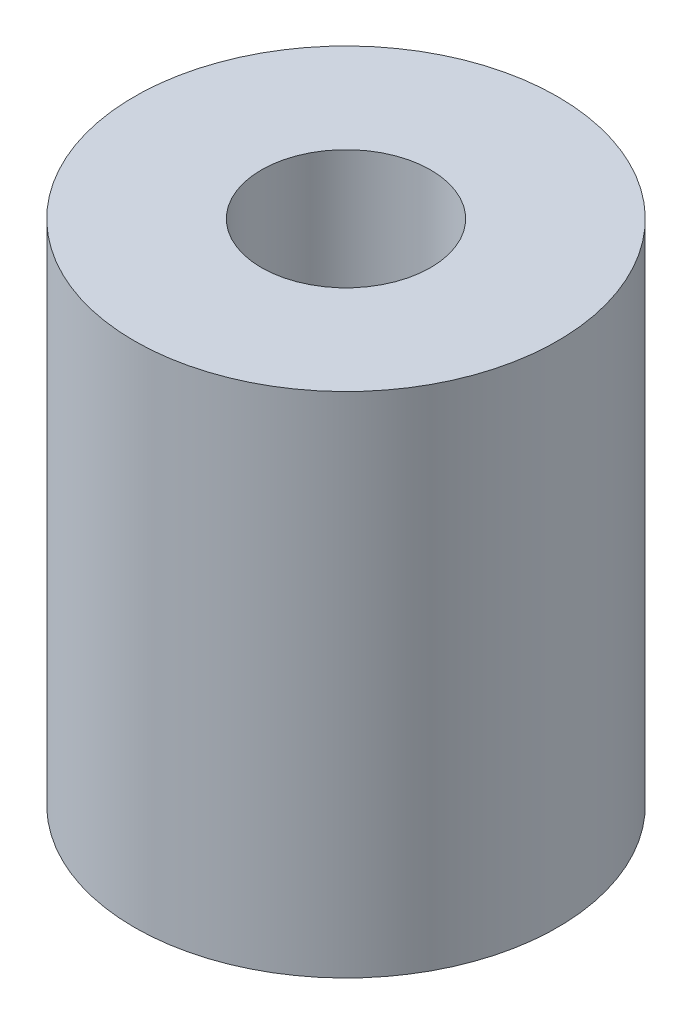
SolidWorks part; units mm, degrees
ref_plane "Front Plane" through (0, 0, 0) normal (0, 0, 1) x (1, 0, 0)
ref_plane "Top Plane" through (0, 0, 0) normal (0, 1, 0) x (1, 0, 0)
ref_plane "Right Plane" through (0, 0, 0) normal (1, 0, 0) x (0, 0, -1)
sketch "Sketch1" plane through (0, 0, 0) normal (0, 1, 0) x (1, 0, 0)
  circle A0 centre (0, 0) radius 5
  dimension "D1" = 10
extrude "Boss-Extrude1" add sketch "Sketch1" along normal blind 12
sketch "Sketch2" plane through (0, 12, 0) normal (0, 1, 0) x (1, 0, 0)
  circle A0 centre (0, 0) radius 2
  dimension "D1" = 4
extrude "Cut-Extrude1" cut sketch "Sketch2" against normal up to next
